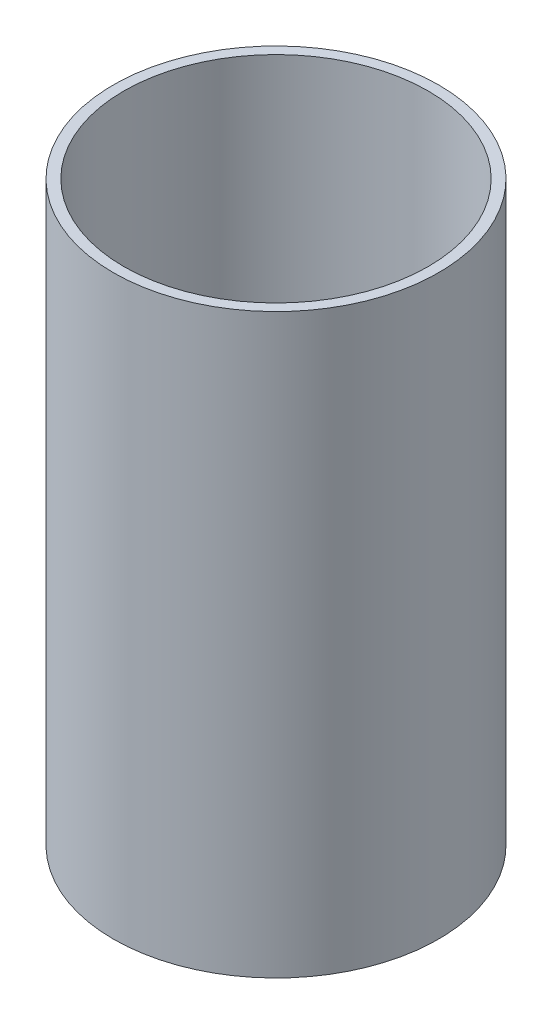
SolidWorks part; units mm, degrees
material "Silicon Dioxide"
ref_plane "Front Plane" through (0, 0, 0) normal (0, 0, 1) x (1, 0, 0)
ref_plane "Top Plane" through (0, 0, 0) normal (0, 1, 0) x (1, 0, 0)
ref_plane "Right Plane" through (0, 0, 0) normal (1, 0, 0) x (0, 0, -1)
sketch "Sketch1" plane through (0, 0, 0) normal (1, 0, 0) x (0, 0, -1)
  line L0 (0, 0) -> (31, 0)
  line L1 (31, 0) -> (31, 110)
  line L2 (31, 110) -> (29, 110)
  line L3 (29, 110) -> (29, 2)
  line L4 (29, 2) -> (0, 2)
  line L5 (0, 2) -> (0, 0)
  dimension "D1" = 31
  dimension "D2" = 2
  dimension "D3" = 110
revolve "Revolve1" add sketch "Sketch1" angle 360 about L5
